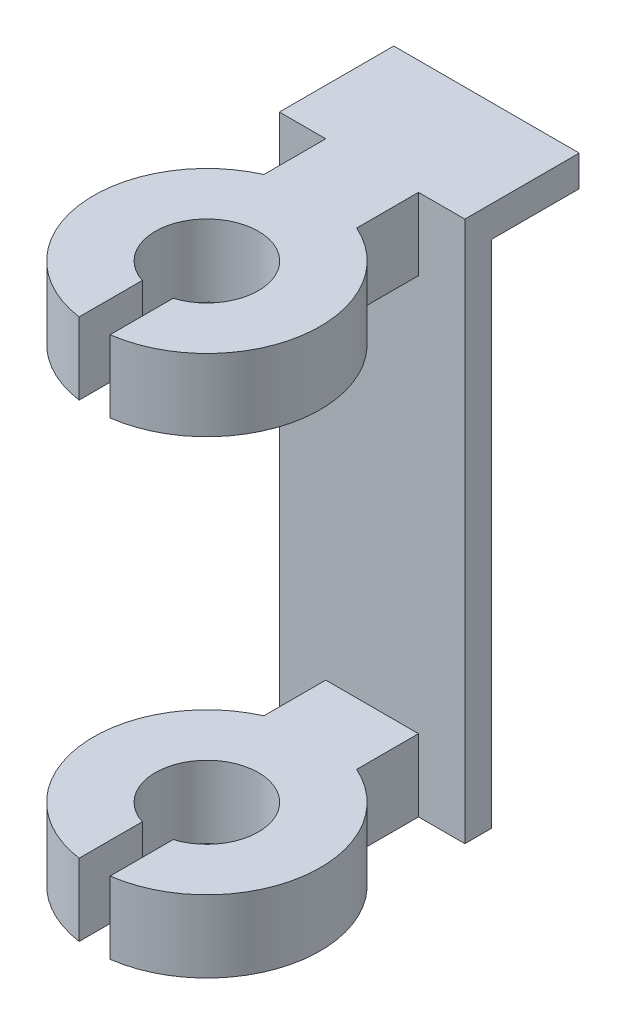
SolidWorks part; units mm, degrees
ref_plane "Front Plane" through (0, 0, 0) normal (0, 0, 1) x (1, 0, 0)
ref_plane "Top Plane" through (0, 0, 0) normal (0, 1, 0) x (1, 0, 0)
ref_plane "Right Plane" through (0, 0, 0) normal (1, 0, 0) x (0, 0, -1)
sketch "Sketch1" plane through (0, 0, 0) normal (0, 1, 0) x (1, 0, 0)
  line L0 (0, 0) -> (0, 21.2887) construction
  line L1 (-11, 0) -> (-11, 13.3572) construction
  line L2 (11, 0) -> (11, 12.1314) construction
  line L3 (4.5, 10.0374) -> (4.5, 16.0374)
  line L4 (-4.5, 10.0374) -> (-4.5, 16.0374)
  line L5 (-4.5, 16.0374) -> (-9, 16.0374)
  line L6 (4.5, 16.0374) -> (9, 16.0374)
  line L10 (0, 18.6374) -> (-9, 18.6374)
  line L11 (0, 18.6374) -> (9, 18.6374)
  line L12 (-9, 18.6374) -> (-9, 16.0374)
  line L13 (9, 18.6374) -> (9, 16.0374)
  line L14 (-1.5, -4.7697) -> (-1.5, -10.8972)
  line L15 (1.5, -4.7697) -> (1.5, -10.8972)
  arc A0 (1.5, -4.7697) -> (-1.5, -4.7697) centre (0, 0) ccw
  arc A1 (-4.5, 10.0374) -> (-1.5, -10.8972) centre (0, 0) ccw
  arc A2 (1.5, -10.8972) -> (4.5, 10.0374) centre (0, 0) ccw
  dimension "D1" = 10
  dimension "D2" = 22
  dimension "D3" = 4.5
  dimension "D4" = 4.5
  dimension "D5" = 6
  dimension "D6" = 6
  dimension "D7" = 9
  dimension "D8" = 9
  dimension "D9" = 2.6
  dimension "D10" = 1.5
  dimension "D11" = 1.5
extrude "Boss-Extrude1" add sketch "Sketch1" along normal blind 7
sketch "Sketch2" plane through (0, 0, 0) normal (0, -1, 0) x (1, 0, 0)
  line L0 (-9, -16.0374) -> (9, -16.0374)
  line L1 (-9, -18.6374) -> (-9, -16.0374) construction
  line L2 (-9, -16.0374) -> (-4.5, -16.0374) construction
  line L3 (9, -16.0374) -> (9, -18.6374)
  line L4 (9, -18.6374) -> (-9, -18.6374)
  line L5 (-9, -18.6374) -> (-9, -16.0374)
extrude "Boss-Extrude2" add sketch "Sketch2" along normal blind 45.5
sketch "Sketch3" plane through (0, 0, -18.6374) normal (0, 0, -1) x (-1, 0, 0)
  line L0 (9, 7) -> (9, -45.5) construction
  line L1 (-9, 7) -> (9, 7)
  line L2 (-9, 7) -> (-9, 4)
  line L3 (-9, 4) -> (9, 4)
  line L4 (9, 7) -> (9, 4)
  dimension "D1" = 3
extrude "Boss-Extrude3" add sketch "Sketch3" along normal blind 8.5
sketch "Sketch5" plane through (0, -45.5, 0) normal (0, -1, 0) x (1, 0, 0)
  line L0 (0, -15.2195) -> (0, -5) construction
  line L2 (0, -16.0374) -> (-4.5, -16.0374)
  line L3 (9, -16.0374) -> (-9, -16.0374) construction
  line L4 (-4.5, -16.0374) -> (-4.5, -10.0374)
  line L5 (0, -16.0374) -> (4.5, -16.0374)
  line L6 (4.5, -16.0374) -> (4.5, -10.0374)
  line L7 (-1.5, 4.7697) -> (-1.5, 10.8972)
  line L8 (1.5, 4.7697) -> (1.5, 10.8972)
  line L9 (0, 11) -> (0, 1022) construction
  arc A0 (-1.5, 4.7697) -> (1.5, 4.7697) centre (0, 0) ccw
  arc A1 (4.5, -10.0374) -> (1.5, 10.8972) centre (0, 0) ccw
  arc A2 (-1.5, 10.8972) -> (-4.5, -10.0374) centre (0, 0) ccw
extrude "Boss-Extrude4" add sketch "Sketch5" against normal blind 7
sketch "Sketch6" plane through (0, 0, -18.6374) normal (0, 0, -1) x (-1, 0, 0)
  text T0 "29"
extrude "Cut-Extrude1" cut sketch "Sketch6" against normal blind 1
